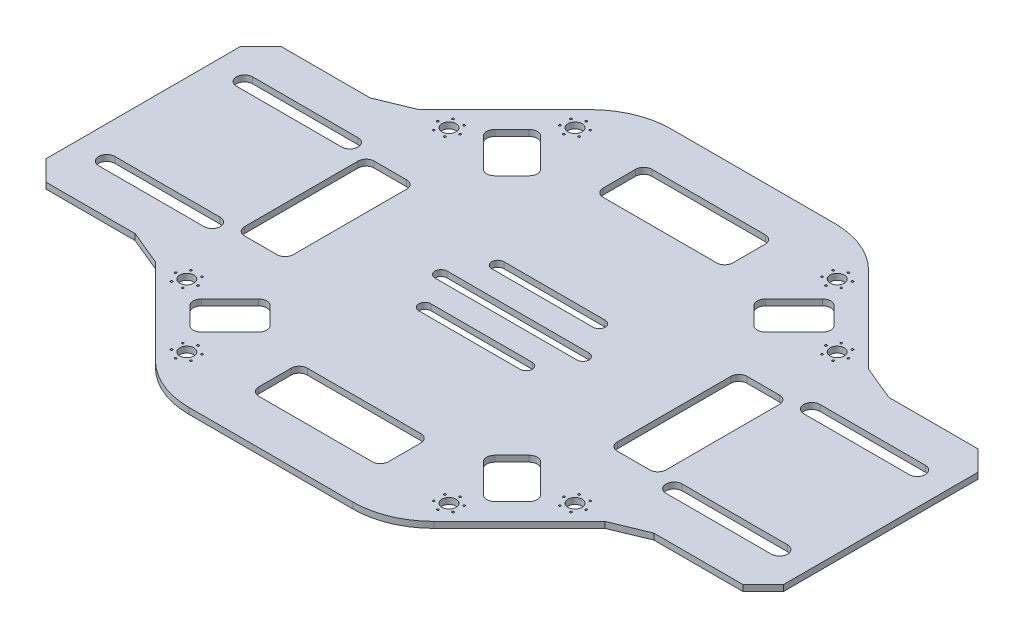
SolidWorks part; units mm, degrees
ref_plane "Front Plane" through (0, 0, 0) normal (0, 0, 1) x (1, 0, 0)
ref_plane "Top Plane" through (0, 0, 0) normal (0, 1, 0) x (1, 0, 0)
ref_plane "Right Plane" through (0, 0, 0) normal (1, 0, 0) x (0, 0, -1)
sketch "Sketch1" plane through (0, 0, 0) normal (0, 1, 0) x (1, 0, 0)
  line L0 (0, 0) -> (0, 340.9146) construction
  line L1 (0, 0) -> (552.6048, 0) construction
  line L2 (28.5, 59.5) -> (-28.5, 59.5)
  line L4 (59, 29) -> (91, 29)
  line L5 (91, 29) -> (91, -29)
  line L6 (59, -29) -> (91, -29)
  line L8 (28.5, -59.5) -> (-28.5, -59.5)
  line L10 (-59, -29) -> (-91, -29)
  line L11 (-91, 29) -> (-91, -29)
  line L12 (-59, 29) -> (-91, 29)
  line L14 (28.5, 59.5) -> (59, 29)
  line L15 (59, -29) -> (28.5, -59.5)
  line L16 (-59, 29) -> (-28.5, 59.5)
  line L17 (-59, -29) -> (-28.5, -59.5)
  point P3 (-91, 0)
  point P10 (91, 0)
  point P14 (0, -59.5)
  point P19 (0, 59.5)
  dimension "D1" = 182
  dimension "D2" = 119
  dimension "D3" = 32
  dimension "D4" = 45
  dimension "D5" = 58
extrude "Boss-Extrude1" add sketch "Sketch1" along normal blind 1.5
chamfer "Chamfer1" distance 5 angle 45 4 edges at (-91, 0.75, -29) (-91, 0.75, 29) (91, 0.75, 29) (91, 0.75, -29)
fillet "Fillet1" radius 20 4 edges at (28.5, 0.75, 59.5) (-28.5, 0.75, 59.5) (-28.5, 0.75, -59.5) (28.5, 0.75, -59.5)
chamfer "Chamfer2" distance 5 4 edges at (59, 0.75, 29) (-59, 0.75, 29) (-59, 0.75, -29) (59, 0.75, -29)
sketch "Sketch3" plane through (0, 1.5, 0) normal (0, 1, 0) x (1, 0, 0)
  line L0 (0, 0) -> (-70.5095, 70.5095) construction
  line L1 (0, 0) -> (72.4144, 72.4144) construction
  line L2 (0, 0) -> (-91, 0) construction
  line L3 (-91, 24) -> (-91, -24) construction
  circle A0 centre (-32.3501, 47.9065) radius 1.75
  circle A1 centre (-47.9065, 32.3501) radius 1.75
  circle A3 centre (32.3501, 47.9065) radius 1.75
  circle A4 centre (47.9065, 32.3501) radius 1.75
  circle A5 centre (47.9065, -32.3501) radius 1.75
  circle A6 centre (32.3501, -47.9065) radius 1.75
  circle A7 centre (-32.3501, -47.9065) radius 1.75
  circle A8 centre (-47.9065, -32.3501) radius 1.75
  point P11 (32.3501, -47.9065)
  point P27 (0, 0)
  dimension "D2" = 3.5
  dimension "D3" = 22
  dimension "D1" = 45
  dimension "D4" = 56.75
  dimension "D5" = 4
extrude "Cut-Extrude1" cut sketch "Sketch3" against normal through all
sketch "Sketch4" plane through (0, 1.5, 0) normal (0, 1, 0) x (1, 0, 0)
  line L0 (57, 17) -> (83, 17) construction
  line L1 (57, 19) -> (83, 19)
  line L2 (57, 15) -> (83, 15)
  line L3 (-17.5, 0) -> (17.5, 0) construction
  line L4 (-17.5, 1.5) -> (17.5, 1.5)
  line L5 (-17.5, -1.5) -> (17.5, -1.5)
  line L6 (-12.5, 9) -> (12.5, 9) construction
  line L7 (-12.5, 10.5) -> (12.5, 10.5)
  line L8 (-12.5, 7.5) -> (12.5, 7.5)
  line L9 (0, 0) -> (109.8094, 0) construction
  line L10 (-16, 48.5) -> (16, 48.5)
  line L11 (-16, 48.5) -> (-16, 36.5)
  line L12 (-16, 36.5) -> (16, 36.5)
  line L13 (16, 48.5) -> (16, 36.5)
  line L14 (40, 16) -> (52, 16)
  line L15 (40, 16) -> (40, -16)
  line L16 (40, -16) -> (52, -16)
  line L17 (52, 16) -> (52, -16)
  line L18 (0, 0) -> (0, 75.8422) construction
  line L19 (91, -24) -> (91, 24) construction
  line L20 (86, 29) -> (64, 29) construction
  line L21 (57, -17) -> (83, -17) construction
  line L22 (57, -19) -> (83, -19)
  line L23 (57, -15) -> (83, -15)
  line L24 (-12.5, -9) -> (12.5, -9) construction
  line L25 (-12.5, -10.5) -> (12.5, -10.5)
  line L26 (-12.5, -7.5) -> (12.5, -7.5)
  line L27 (20.2157, 59.5) -> (-20.2157, 59.5) construction
  line L28 (-40, -16) -> (-52, -16)
  line L29 (-40, 16) -> (-40, -16)
  line L30 (-40, 16) -> (-52, 16)
  line L31 (-52, 16) -> (-52, -16)
  line L32 (-57, -17) -> (-83, -17) construction
  line L33 (-57, -19) -> (-83, -19)
  line L34 (-57, -15) -> (-83, -15)
  line L35 (-57, 17) -> (-83, 17) construction
  line L36 (-57, 19) -> (-83, 19)
  line L37 (-57, 15) -> (-83, 15)
  line L38 (16, -48.5) -> (16, -36.5)
  line L39 (-16, -48.5) -> (16, -48.5)
  line L40 (-16, -48.5) -> (-16, -36.5)
  line L41 (-16, -36.5) -> (16, -36.5)
  arc A0 (57, 19) -> (57, 15) centre (57, 17) ccw
  arc A1 (83, 15) -> (83, 19) centre (83, 17) ccw
  arc A2 (-17.5, 1.5) -> (-17.5, -1.5) centre (-17.5, 0) ccw
  arc A3 (17.5, -1.5) -> (17.5, 1.5) centre (17.5, 0) ccw
  arc A4 (-12.5, 10.5) -> (-12.5, 7.5) centre (-12.5, 9) ccw
  arc A5 (12.5, 7.5) -> (12.5, 10.5) centre (12.5, 9) ccw
  arc A6 (57, -19) -> (57, -15) centre (57, -17) cw
  arc A7 (83, -15) -> (83, -19) centre (83, -17) cw
  arc A8 (-12.5, -10.5) -> (-12.5, -7.5) centre (-12.5, -9) cw
  arc A9 (12.5, -7.5) -> (12.5, -10.5) centre (12.5, -9) cw
  arc A10 (-57, -19) -> (-57, -15) centre (-57, -17) ccw
  arc A11 (-83, -15) -> (-83, -19) centre (-83, -17) ccw
  arc A12 (-57, 19) -> (-57, 15) centre (-57, 17) cw
  arc A13 (-83, 15) -> (-83, 19) centre (-83, 17) cw
  point P2 (70, 17)
  point P7 (0, 0)
  point P15 (0, 9)
  point P41 (70, -17)
  point P52 (0, -9)
  point P65 (-70, -17)
  point P72 (-70, 17)
  dimension "D7" = 2
  dimension "D10" = 1.5
  dimension "D12" = 1.5
  dimension "D1" = 12
  dimension "D2" = 32
  dimension "D3" = 12
  dimension "D4" = 32
  dimension "D5" = 39
  dimension "D6" = 26
  dimension "D8" = 8
  dimension "D9" = 10
  dimension "D11" = 35
  dimension "D13" = 25
  dimension "D14" = 6
  dimension "D15" = 11
extrude "Cut-Extrude2" cut sketch "Sketch4" against normal blind 1.5
fillet "Fillet2" radius 2 16 edges at (-40, 0.75, -16) (-40, 0.75, 16) (-52, 0.75, 16) (-52, 0.75, -16) (16, 0.75, 36.5) (16, 0.75, 48.5) (-16, 0.75, 48.5) (-16, 0.75, 36.5) (52, 0.75, 16) (40, 0.75, 16) (40, 0.75, -16) (52, 0.75, -16) (-16, 0.75, -36.5) (16, 0.75, -36.5) (16, 0.75, -48.5) (-16, 0.75, -48.5)
sketch "Sketch5" plane through (0, 1.5, 0) normal (0, 1, 0) x (1, 0, 0)
  line L0 (0, 0) -> (-59.8676, 59.8676) construction
  line L1 (-41.8787, 37.636) -> (-37.636, 41.8787)
  line L2 (-34.8076, 41.8787) -> (-27.7365, 34.8076)
  line L3 (-27.7365, 31.9792) -> (-31.9792, 27.7365)
  line L4 (-34.8076, 27.7365) -> (-41.8787, 34.8076)
  line L5 (-34.3579, 53.6421) -> (-55.4645, 32.5355) construction
  line L6 (31.9792, 27.7365) -> (27.7365, 31.9792)
  line L7 (27.7365, 34.8076) -> (34.8076, 41.8787)
  line L8 (37.636, 41.8787) -> (41.8787, 37.636)
  line L9 (41.8787, 34.8076) -> (34.8076, 27.7365)
  line L10 (27.7365, -31.9792) -> (31.9792, -27.7365)
  line L11 (34.8076, -27.7365) -> (41.8787, -34.8076)
  line L12 (41.8787, -37.636) -> (37.636, -41.8787)
  line L13 (34.8076, -41.8787) -> (27.7365, -34.8076)
  line L14 (-31.9792, -27.7365) -> (-27.7365, -31.9792)
  line L15 (-27.7365, -34.8076) -> (-34.8076, -41.8787)
  line L16 (-37.636, -41.8787) -> (-41.8787, -37.636)
  line L17 (-41.8787, -34.8076) -> (-34.8076, -27.7365)
  arc A0 (-41.8787, 37.636) -> (-41.8787, 34.8076) centre (-40.4645, 36.2218) ccw
  arc A1 (-31.9792, 27.7365) -> (-34.8076, 27.7365) centre (-33.3934, 29.1508) cw
  arc A2 (-27.7365, 34.8076) -> (-27.7365, 31.9792) centre (-29.1508, 33.3934) cw
  arc A3 (-37.636, 41.8787) -> (-34.8076, 41.8787) centre (-36.2218, 40.4645) cw
  arc A4 (34.8076, 27.7365) -> (31.9792, 27.7365) centre (33.3934, 29.1508) cw
  arc A5 (27.7365, 31.9792) -> (27.7365, 34.8076) centre (29.1508, 33.3934) cw
  arc A6 (37.636, 41.8787) -> (34.8076, 41.8787) centre (36.2218, 40.4645) ccw
  arc A7 (41.8787, 37.636) -> (41.8787, 34.8076) centre (40.4645, 36.2218) cw
  arc A8 (27.7365, -34.8076) -> (27.7365, -31.9792) centre (29.1508, -33.3934) cw
  arc A9 (31.9792, -27.7365) -> (34.8076, -27.7365) centre (33.3934, -29.1508) cw
  arc A10 (41.8787, -37.636) -> (41.8787, -34.8076) centre (40.4645, -36.2218) ccw
  arc A11 (37.636, -41.8787) -> (34.8076, -41.8787) centre (36.2218, -40.4645) cw
  arc A12 (-34.8076, -27.7365) -> (-31.9792, -27.7365) centre (-33.3934, -29.1508) cw
  arc A13 (-27.7365, -31.9792) -> (-27.7365, -34.8076) centre (-29.1508, -33.3934) cw
  arc A14 (-37.636, -41.8787) -> (-34.8076, -41.8787) centre (-36.2218, -40.4645) ccw
  arc A15 (-41.8787, -37.636) -> (-41.8787, -34.8076) centre (-40.4645, -36.2218) cw
  point P56 (0, 0)
  dimension "D4" = 2
  dimension "D1" = 6
  dimension "D2" = 10
  dimension "D3" = 14
  dimension "D5" = 4
extrude "Cut-Extrude3" cut sketch "Sketch5" against normal blind 1.5
sketch "Sketch6" plane through (0, 1.5, 0) normal (0, 1, 0) x (1, 0, 0)
  line L0 (-29.8579, 29.8579) -> (-39.7574, 39.7574) construction
  line L1 (-31.9792, 27.7365) -> (-27.7365, 31.9792) construction
  line L2 (-37.636, 41.8787) -> (-41.8787, 37.636) construction
  circle A0 centre (-32.3501, 47.9065) radius 2.75 construction
  circle A1 centre (-32.3501, 50.6565) radius 0.25
  circle A2 centre (-29.9686, 49.2815) radius 0.25
  circle A3 centre (-29.9686, 46.5315) radius 0.25
  circle A4 centre (-32.3501, 45.1565) radius 0.25
  circle A5 centre (-34.7317, 46.5315) radius 0.25
  circle A6 centre (-34.7317, 49.2815) radius 0.25
  circle A7 centre (-49.2815, 34.7317) radius 0.25
  circle A8 centre (-46.5315, 34.7317) radius 0.25
  circle A9 centre (-45.1565, 32.3501) radius 0.25
  circle A10 centre (-46.5315, 29.9686) radius 0.25
  circle A11 centre (-49.2815, 29.9686) radius 0.25
  circle A12 centre (-50.6565, 32.3501) radius 0.25
  circle A13 centre (-50.6565, -32.3501) radius 0.25
  circle A14 centre (-49.2815, -29.9686) radius 0.25
  circle A15 centre (-46.5315, -29.9686) radius 0.25
  circle A16 centre (-45.1565, -32.3501) radius 0.25
  circle A17 centre (-46.5315, -34.7317) radius 0.25
  circle A18 centre (-49.2815, -34.7317) radius 0.25
  circle A19 centre (-34.7317, -46.5315) radius 0.25
  circle A20 centre (-32.3501, -45.1565) radius 0.25
  circle A21 centre (-29.9686, -46.5315) radius 0.25
  circle A22 centre (-29.9686, -49.2815) radius 0.25
  circle A23 centre (-32.3501, -50.6565) radius 0.25
  circle A24 centre (-34.7317, -49.2815) radius 0.25
  circle A25 centre (32.3501, -50.6565) radius 0.25
  circle A26 centre (29.9686, -49.2815) radius 0.25
  circle A27 centre (29.9686, -46.5315) radius 0.25
  circle A28 centre (32.3501, -45.1565) radius 0.25
  circle A29 centre (34.7317, -46.5315) radius 0.25
  circle A30 centre (34.7317, -49.2815) radius 0.25
  circle A31 centre (46.5315, -34.7317) radius 0.25
  circle A32 centre (45.1565, -32.3501) radius 0.25
  circle A33 centre (46.5315, -29.9686) radius 0.25
  circle A34 centre (49.2815, -29.9686) radius 0.25
  circle A35 centre (50.6565, -32.3501) radius 0.25
  circle A36 centre (49.2815, -34.7317) radius 0.25
  circle A37 centre (50.6565, 32.3501) radius 0.25
  circle A38 centre (49.2815, 29.9686) radius 0.25
  circle A39 centre (46.5315, 29.9686) radius 0.25
  circle A40 centre (45.1565, 32.3501) radius 0.25
  circle A41 centre (46.5315, 34.7317) radius 0.25
  circle A42 centre (49.2815, 34.7317) radius 0.25
  circle A43 centre (34.7317, 46.5315) radius 0.25
  circle A44 centre (32.3501, 45.1565) radius 0.25
  circle A45 centre (29.9686, 46.5315) radius 0.25
  circle A46 centre (29.9686, 49.2815) radius 0.25
  circle A47 centre (32.3501, 50.6565) radius 0.25
  circle A48 centre (34.7317, 49.2815) radius 0.25
  point P17 (-32.3501, 47.9065)
  point P109 (0, 0)
  dimension "D1" = 5.5
  dimension "D2" = 0.5
  dimension "D3" = 6
  dimension "D4" = 4
extrude "Cut-Extrude4" cut sketch "Sketch6" against normal blind 1.5
